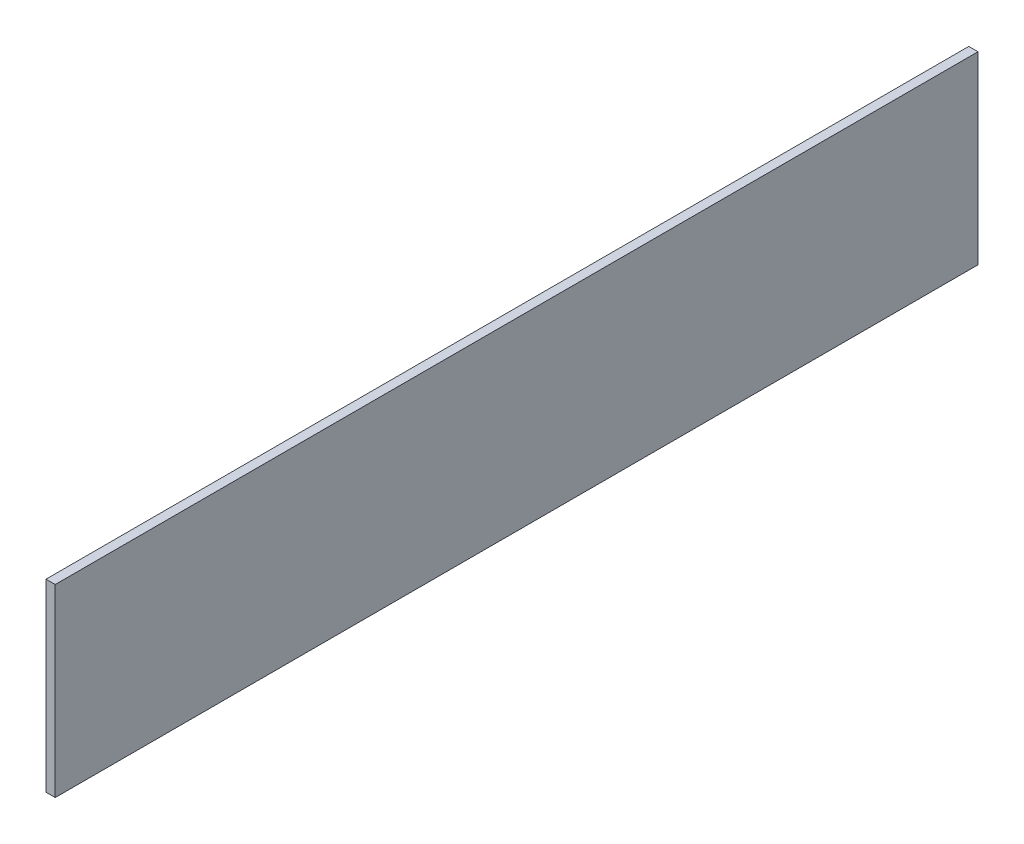
SolidWorks part; units mm, degrees
ref_plane "Plan de face" through (0, 0, 0) normal (0, 0, 1) x (1, 0, 0)
ref_plane "Plan de dessus" through (0, 0, 0) normal (0, 1, 0) x (1, 0, 0)
ref_plane "Plan de droite" through (0, 0, 0) normal (1, 0, 0) x (0, 0, -1)
sketch "Esquisse1" plane through (0, 0, 0) normal (1, 0, 0) x (0, 0, -1)
  line L1 (-100, -20) -> (100, -20)
  line L2 (-100, -20) -> (-100, 20)
  line L3 (-100, 20) -> (100, 20)
  line L4 (100, -20) -> (100, 20)
  line L5 (-100, -20) -> (100, 20) construction
  line L6 (-100, 20) -> (100, -20) construction
  point P0 (0, 0)
  dimension "D1" = 40
  dimension "D2" = 200
extrude "Boss.-Extru.1" add sketch "Esquisse1" along normal blind 2
